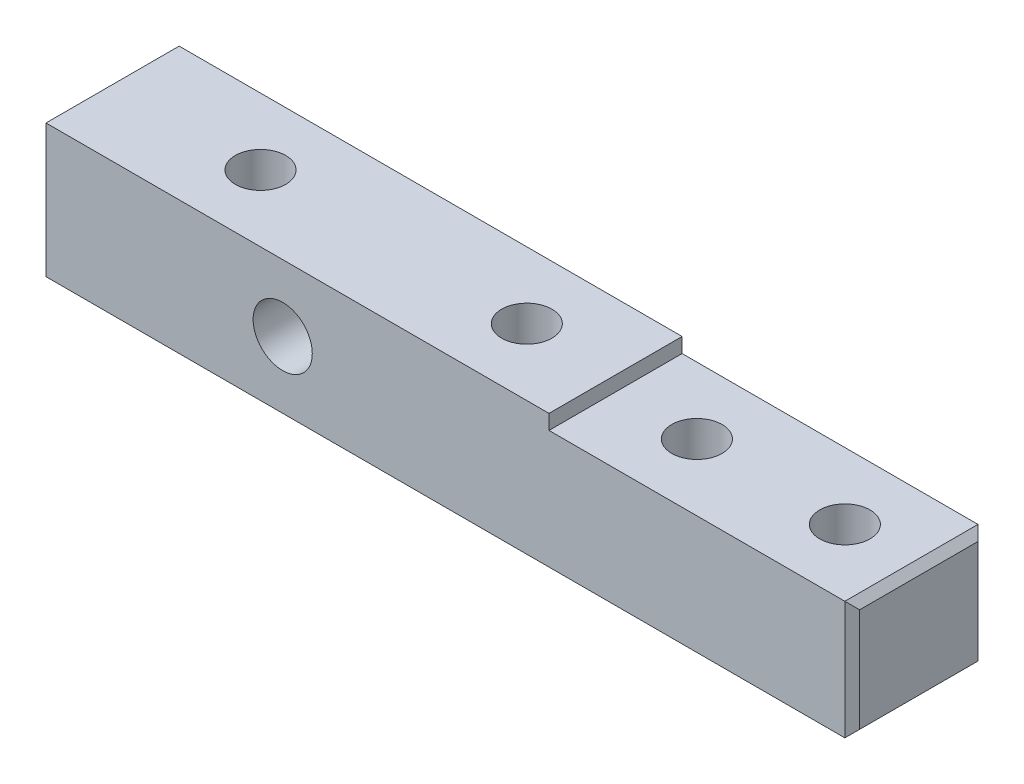
SolidWorks part; units mm, degrees
ref_plane "Front Plane" through (0, 0, 0) normal (0, 0, 1) x (1, 0, 0)
ref_plane "Top Plane" through (0, 0, 0) normal (0, 1, 0) x (1, 0, 0)
ref_plane "Right Plane" through (0, 0, 0) normal (1, 0, 0) x (0, 0, -1)
sketch "Sketch1" plane through (0, 0, 0) normal (0, 0, 1) x (1, 0, 0)
  line L1 (0, 9) -> (110, 9)
  line L2 (0, 9) -> (0, -9)
  line L3 (0, -9) -> (110, -9)
  line L4 (110, 9) -> (110, -9)
  point P4 (0, 0)
  dimension "D1" = 18
  dimension "D2" = 110
extrude "Boss-Extrude1" add sketch "Sketch1" along normal mid plane 18
sketch "Sketch2" plane through (0, 0, 9) normal (0, 0, 1) x (1, 0, 0)
  line L0 (0, -9) -> (110, -9) construction
  line L1 (110, 9) -> (69, 9)
  line L2 (110, 9) -> (110, 7)
  line L3 (110, 7) -> (69, 7)
  line L4 (69, 9) -> (69, 7)
  dimension "D1" = 16
  dimension "D2" = 41
extrude "Cut-Extrude1" cut sketch "Sketch2" against normal through all
hole_wizard "Ø8.0 (8) Diameter Hole1" positions "Sketch3" profile "Sketch4" hole size "Ø8.0" standard "ISO" end condition through all
sketch "Sketch3" plane through (0, 0, 9) normal (0, 0, 1) x (1, 0, 0)
  line L0 (110, -9) -> (110, 7) construction
  point P0 (33, 0)
  dimension "D1" = 77
sketch "Sketch4" plane through (33, 0, 9) normal (1, 0, 0) x (0, -1, 0)
  line L0 (0, 0) -> (0, 18)
  line L1 (0, 18) -> (4, 18)
  line L2 (4, 18) -> (4, 0)
  line L5 (4, 0) -> (0, 0)
  line L11 (0, -6.35) -> (0, 107.95) construction
  dimension "Thru Hole Dia." = 8
  dimension "Thru Hole Depth" = 18
sketch "Sketch5" plane through (0, 9, 0) normal (0, 1, 0) x (1, 0, 0)
  line L0 (110, 9) -> (110, -9) construction
  point P0 (21, 0)
  point P1 (57, 0)
  point P2 (80, 0)
  point P3 (100, 0)
  dimension "D1" = 10
  dimension "D2" = 20
  dimension "D3" = 23
  dimension "D4" = 36
hole_wizard "M8 Tapped Hole1" positions "Sketch6" profile "Sketch7" tap size "M8" standard "ISO" end condition through all
sketch "Sketch6" plane through (0, 9, 0) normal (0, 1, 0) x (1, 0, 0)
  point P0 (21, 0)
  point P3 (57, 0)
  point P6 (80, 0)
  point P9 (100, 0)
sketch "Sketch7" plane through (21, 9, 0) normal (1, 0, 0) x (0, 0, 1)
  line L0 (0, 0) -> (0, 18)
  line L1 (0, 18) -> (3.4, 18)
  line L2 (3.4, 18) -> (3.4, 0)
  line L5 (3.4, 0) -> (0, 0)
  line L11 (0, -6.35) -> (0, 107.95) construction
  dimension "Thru Tap Drill Dia." = 6.8
  dimension "Thru Tap Drill Depth" = 18
cosmetic thread "Hole Thread1" parameters "D2"=8
cosmetic thread "Hole Thread2" parameters "D2"=8
cosmetic thread "Hole Thread3" parameters "D2"=8
cosmetic thread "Hole Thread4" parameters "D2"=8
chamfer "Chamfer1" distance 1 8 edges at (110, -9, 0) (110, -1, -9) (110, 7, 0) (110, -1, 9) (0, -9, 0) (0, 0, -9) (0, 9, 0) (0, 0, 9)
